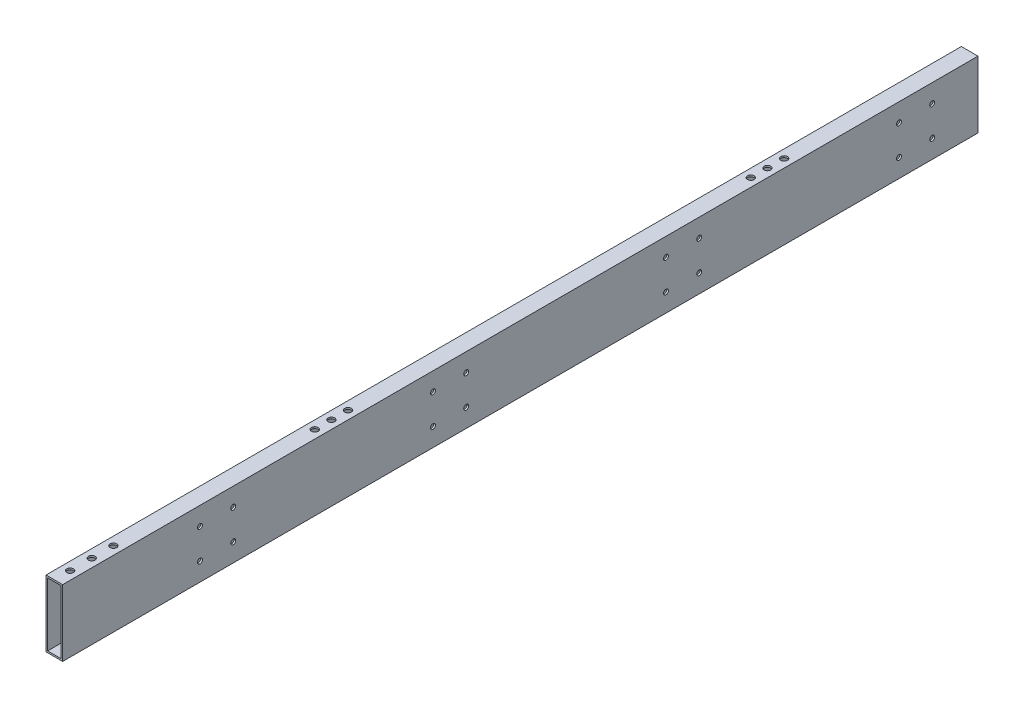
SolidWorks part; units mm, degrees
material "3.0205 (EN-AW 1200)"
ref_plane "前视基准面" through (0, 0, 0) normal (0, 0, 1) x (1, 0, 0)
ref_plane "上视基准面" through (0, 0, 0) normal (0, 1, 0) x (1, 0, 0)
ref_plane "右视基准面" through (0, 0, 0) normal (1, 0, 0) x (0, 0, -1)
sketch "草图1" plane through (0, 0, 0) normal (0, 0, 1) x (1, 0, 0)
  line L1 (-5, 20) -> (5, 20)
  line L2 (-5, 20) -> (-5, -20)
  line L3 (-5, -20) -> (5, -20)
  line L4 (5, 20) -> (5, -20)
  line L5 (-5, 20) -> (5, -20) construction
  line L6 (-5, -20) -> (5, 20) construction
  line L7 (-4, 19) -> (4, 19)
  line L8 (-4, 19) -> (-4, -19)
  line L9 (-4, -19) -> (4, -19)
  line L10 (4, 19) -> (4, -19)
  line L11 (-4, 19) -> (4, -19) construction
  line L12 (-4, -19) -> (4, 19) construction
  point P0 (0, 0)
  point P6 (0, 0)
  dimension "D1" = 10
  dimension "D2" = 40
  dimension "D3" = 38
  dimension "D4" = 8
extrude "凸台-拉伸1" add sketch "草图1" along normal blind 550
sketch "Sketch1" plane through (5, 0, 0) normal (1, 0, 0) x (0, 0, -1)
  line L0 (0, 9) -> (-550, 9) construction
  line L1 (0, -20) -> (0, 20) construction
  line L2 (-550, -20) -> (-550, 20) construction
  line L3 (-550, -9) -> (0, -9) construction
  line L4 (-550, 20) -> (0, 20) construction
  line L5 (-550, -20) -> (0, -20) construction
  circle A0 centre (-27.5, 9) radius 1.5
  circle A1 centre (-47.5, 9) radius 1.5
  circle A2 centre (-27.5, -9) radius 1.5
  circle A3 centre (-47.5, -9) radius 1.5
  dimension "D6" = 20
  dimension "D7" = 3
  dimension "D8" = 3
  dimension "D9" = 3
  dimension "D10" = 3
  dimension "D1" = 11
  dimension "D2" = 11
  dimension "D3" = 27.5
  dimension "D4" = 27.5
  dimension "D5" = 20
extrude "Cut-Extrude1" cut sketch "Sketch1" against normal blind 10
pattern_linear "LPattern1" count 4 spacing 140 along (0, 0, 1) of "Cut-Extrude1"
sketch "Sketch2" plane through (0, 20, 0) normal (0, 1, 0) x (1, 0, 0)
  line L0 (0, 0) -> (0, -550) construction
  line L1 (5, -550) -> (-5, -550) construction
  circle A0 centre (0, -111.5) radius 2
  circle A1 centre (0, -121.5) radius 2
  circle A2 centre (0, -131.5) radius 2
  circle A3 centre (0, -373.5) radius 2
  circle A4 centre (0, -383.5) radius 2
  circle A5 centre (0, -393.5) radius 2
  dimension "D1" = 4
  dimension "D2" = 4
  dimension "D3" = 4
  dimension "D4" = 111.5
  dimension "D8" = 10
  dimension "D9" = 4
  dimension "D10" = 4
  dimension "D11" = 4
  dimension "D12" = 242
  dimension "D5" = 10
  dimension "D6" = 10
  dimension "D7" = 10
extrude "Cut-Extrude2" cut sketch "Sketch2" against normal blind 40
sketch "Sketch3" plane through (0, 20, 0) normal (0, 1, 0) x (1, 0, 0)
  line L0 (0, -550) -> (0, -494.0177) construction
  line L1 (5, -550) -> (-5, -550) construction
  circle A0 centre (0, -540.5) radius 2
  circle A1 centre (0, -527.5) radius 2
  circle A2 centre (0, -514.5) radius 2
  dimension "D1" = 4
  dimension "D2" = 4
  dimension "D3" = 4
  dimension "D4" = 9.5
  dimension "D5" = 13
  dimension "D6" = 13
extrude "Cut-Extrude3" cut sketch "Sketch3" against normal blind 40
